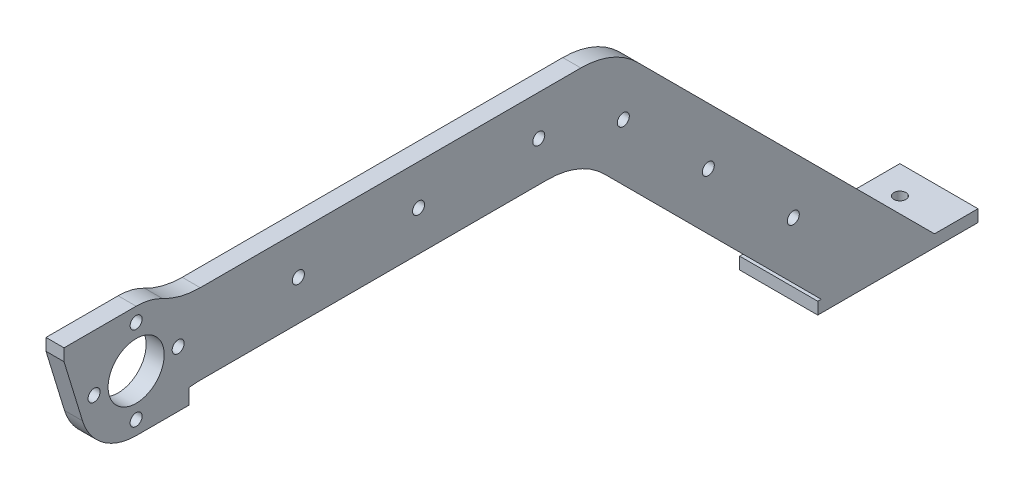
SolidWorks part; units mm, degrees
ref_plane "前视基准面" through (0, 0, 0) normal (0, 0, 1) x (1, 0, 0)
ref_plane "上视基准面" through (0, 0, 0) normal (0, 1, 0) x (1, 0, 0)
ref_plane "右视基准面" through (0, 0, 0) normal (1, 0, 0) x (0, 0, -1)
sketch "草图1" plane through (0, 0, 0) normal (1, 0, 0) x (0, 0, -1)
  line L2 (116.8579, -15.8579) -> (171, -70)
  line L3 (171, -70) -> (199.2843, -70)
  line L4 (199.2843, -70) -> (125.1421, 4.1421)
  line L5 (111, 10) -> (16, 10)
  line L7 (16, -10) -> (102.7369, -10)
  line L8 (186.193, -71.0509) -> (123.8062, -8.664) construction
  line L9 (0, 14) -> (-18, 14)
  line L10 (-18, 14) -> (-18, 11)
  line L11 (-18, 11) -> (-13.3889, -4.091)
  line L12 (13.2242, -14) -> (13.2242, -10)
  line L13 (0, -14) -> (13.2242, -14)
  arc A0 (6.5882, 12.3529) -> (6.5882, -12.3529) centre (0, 0) ccw
  circle A1 centre (0, 0) radius 10.5 construction
  circle A2 centre (0, 0) radius 7
  circle A3 centre (0, 10.5) radius 1.5
  circle A4 centre (10.5, 0) radius 1.5
  circle A5 centre (0, -10.5) radius 1.5
  circle A6 centre (-10.5, 0) radius 1.5
  arc A7 (125.1421, 4.1421) -> (111, 10) centre (111, -10) ccw
  arc A8 (102.7369, -10) -> (116.8579, -15.8579) centre (102.7157, -30) cw
  circle A9 centre (40.5, 0) radius 1.5
  circle A10 centre (70.5, 0) radius 1.5
  circle A11 centre (100.5, 0) radius 1.5
  circle A12 centre (121.61, -6.4679) radius 1.5
  circle A13 centre (142.8232, -27.6811) radius 1.5
  circle A14 centre (164.0364, -48.8943) radius 1.5
  arc A15 (16, 10) -> (6.5882, 12.3529) centre (16, 30) cw
  arc A16 (16, -10) -> (6.5882, -12.3529) centre (16, -30) ccw
  point P36 (185.1421, -70)
  point P43 (9.798, 7.7889)
  point P50 (9.798, -10)
  dimension "D1" = 28
  dimension "D2" = 21
  dimension "D3" = 14
  dimension "D4" = 3
  dimension "D9" = 20
  dimension "D13" = 3
  dimension "D16" = 30
  dimension "D17" = 3
  dimension "D19" = 30
  dimension "D24" = 20
  dimension "D25" = 20
  dimension "D6" = 135
  dimension "D7" = 20
  dimension "D8" = 171
  dimension "D10" = 70
  dimension "D11" = 20
  dimension "D14" = 40.5
  dimension "D18" = 21.11
  dimension "D20" = 30
  dimension "D21" = 18
  dimension "D22" = 3
  dimension "D26" = 13.2242
  dimension "D28" = 20
  dimension "D15" = 3
  dimension "D5" = 4
extrude "凸台-拉伸1" add sketch "草图1" along normal mid plane 4.5
sketch "草图3" plane through (0, -70, 0) normal (0, -1, 0) x (1, 0, 0)
  line L0 (2.25, -116.8579) -> (2.25, -171) construction
  line L1 (2.25, -170.1443) -> (-17.25, -170.1443)
  line L2 (2.25, -170.1443) -> (2.25, -210.1443)
  line L3 (2.25, -210.1443) -> (-17.25, -210.1443)
  line L4 (-17.25, -170.1443) -> (-17.25, -210.1443)
  dimension "D1" = 19.5
  dimension "D2" = 40
  dimension "D3" = 10.86
extrude "凸台-拉伸2" add sketch "草图3" along normal blind 3
sketch "草图4" plane through (0, -70, 0) normal (0, 1, 0) x (1, 0, 0)
  line L0 (-17.25, 190.1443) -> (2.25, 190.1443) construction
  line L1 (-17.25, 170.1443) -> (-17.25, 210.1443) construction
  line L2 (2.25, 199.2843) -> (2.25, 125.1421) construction
  line L3 (-17.25, 210.1443) -> (2.25, 210.1443) construction
  circle A0 centre (-10.25, 203.1443) radius 1.5
  circle A1 centre (-10.25, 177.1443) radius 1.5
  dimension "D1" = 3
  dimension "D2" = 7
  dimension "D3" = 7
extrude "切除-拉伸1" cut sketch "草图4" against normal through all
